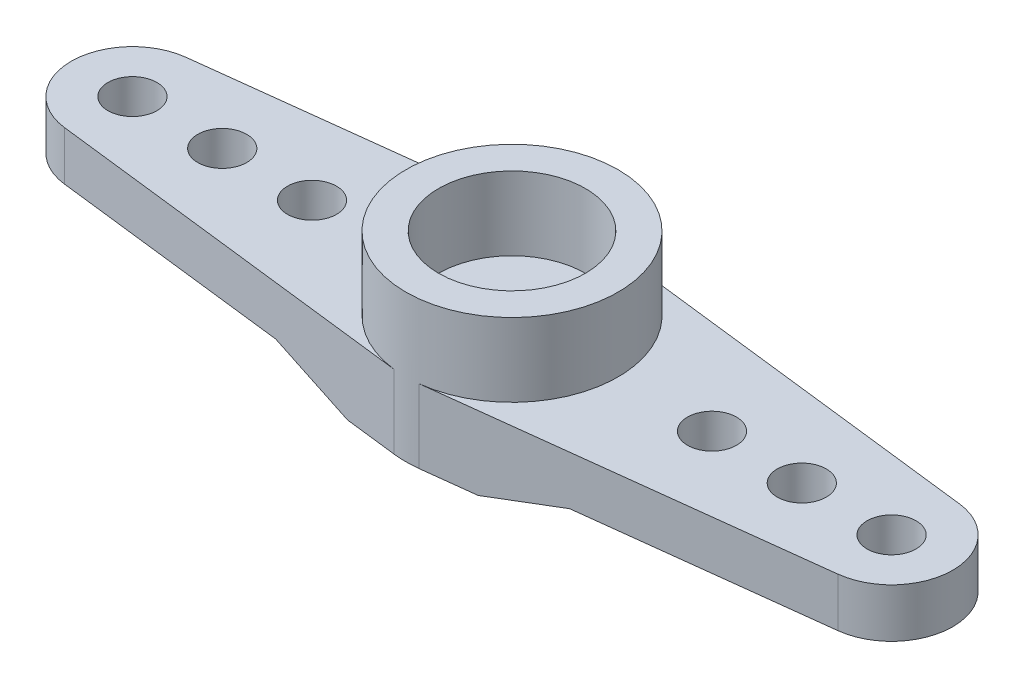
SolidWorks part; units mm, degrees
ref_plane "Alzado" through (0, 0, 0) normal (0, 0, 1) x (1, 0, 0)
ref_plane "Planta" through (0, 0, 0) normal (0, 1, 0) x (1, 0, 0)
ref_plane "Vista lateral" through (0, 0, 0) normal (1, 0, 0) x (0, 0, -1)
sketch "Croquis1" plane through (0, 0, 0) normal (0, 1, 0) x (1, 0, 0)
  line L0 (-30.9646, 0) -> (30.9646, 0) construction
  line L1 (0, -23.5018) -> (0, 23.5018) construction
  line L2 (0.7688, 6.4544) -> (23.6935, 3.7237)
  line L3 (0.7688, -6.4544) -> (23.6935, -3.7237)
  line L4 (-0.7688, -6.4544) -> (-23.6935, -3.7237)
  line L5 (-0.7688, 6.4544) -> (-23.6935, 3.7237)
  arc A0 (-0.7688, -6.4544) -> (0.7688, -6.4544) centre (0, 0) ccw
  arc A1 (23.6935, -3.7237) -> (23.6935, 3.7237) centre (23.25, 0) ccw
  arc A2 (0.7688, 6.4544) -> (-0.7688, 6.4544) centre (0, 0) ccw
  arc A3 (-23.6935, -3.7237) -> (-23.6935, 3.7237) centre (-23.25, 0) cw
  point P6 (0, 0)
  point P11 (27, 0)
  dimension "D1" = 13
  dimension "D3" = 27
  dimension "D2" = 23.25
extrude "Saliente-Extruir1" add sketch "Croquis1" along normal blind 3
sketch "Croquis2" plane through (0, 3, 0) normal (0, 1, 0) x (1, 0, 0)
  arc A0 (0.7688, 6.4544) -> (-0.7688, 6.4544) centre (0, 0) ccw construction
  arc A1 (0.7688, 6.4544) -> (-0.7688, 6.4544) centre (0, 0) ccw construction
  circle A2 centre (0, 0) radius 6.5
  circle A3 centre (0, 0) radius 4.5
  dimension "D1" = 9
extrude "Saliente-Extruir2" add sketch "Croquis2" along normal blind 4.5
sketch "Croquis3" plane through (0, 0, 0) normal (0, -1, 0) x (1, 0, 0)
  line L0 (23.6935, -3.7237) -> (0.7688, -6.4544) construction
  line L1 (-0.7688, -6.4544) -> (-23.6935, -3.7237) construction
  line L2 (0.7688, 6.4544) -> (23.6935, 3.7237) construction
  line L3 (-23.6935, 3.7237) -> (-0.7688, 6.4544) construction
  line L4 (4, -6.0695) -> (0.7688, -6.4544)
  line L5 (-0.7688, -6.4544) -> (-4, -6.0695)
  line L6 (0.7688, 6.4544) -> (4, 6.0695)
  line L7 (-4, 6.0695) -> (-0.7688, 6.4544)
  line L8 (0, 8.9582) -> (0, -10.3937) construction
  line L9 (-4, 6.0695) -> (-4, -6.0695)
  line L10 (4, 6.0695) -> (4, -6.0695)
  arc A0 (-0.7688, -6.4544) -> (0.7688, -6.4544) centre (0, 0) ccw construction
  arc A1 (0.7688, 6.4544) -> (-0.7688, 6.4544) centre (0, 0) ccw construction
  arc A2 (-0.7688, -6.4544) -> (0.7688, -6.4544) centre (0, 0) ccw
  arc A3 (0.7688, 6.4544) -> (-0.7688, 6.4544) centre (0, 0) ccw
  dimension "D1" = 4
extrude "Saliente-Extruir3" add sketch "Croquis3" along normal blind 1.5
sketch "Croquis4" plane through (0, 0, 0) normal (0, 0, 1) x (1, 0, 0)
  line L1 (4, -1.5) -> (4, 0) construction
  line L2 (-4, -1.5) -> (-4, 0) construction
  line L3 (-23.6935, 0) -> (-4, 0) construction
  line L6 (-4, -1.5) -> (-4, 0)
  line L7 (-9, 0) -> (-4, 0)
  line L8 (0, -4.7923) -> (0, 8.7073) construction
  line L9 (-4, -1.5) -> (-9, 0)
  dimension "D1" = 9
extrude "Saliente-Extruir4" add sketch "Croquis4" along normal up to surface and the other way up to surface up to face at (-9.4875, 0.5, 5.4158) other way up to face at (-9.4875, 0.5, -5.4158)
sketch "Croquis5" plane through (0, 0, 0) normal (0, 0, 1) x (1, 0, 0)
  line L0 (4, 0) -> (23.6935, 0) construction
  line L1 (4, -1.5) -> (4, 0) construction
  line L2 (4, 0) -> (9, 0)
  line L3 (4, -1.5) -> (4, 0)
  line L4 (4, -1.5) -> (9, 0)
  dimension "D1" = 9
extrude "Saliente-Extruir5" add sketch "Croquis5" along normal up to surface and the other way up to surface up to face at (9.4875, 0.5, 5.4158) other way up to face at (9.4875, 0.5, -5.4158)
sketch "Croquis7" plane through (0, -1.5, 0) normal (0, -1, 0) x (1, 0, 0)
  circle A0 centre (0, 0) radius 3.5
  dimension "D1" = 7
extrude "Cortar-Extruir1" cut sketch "Croquis7" against normal blind 2.5
sketch "Croquis8" plane through (0, 1, 0) normal (0, -1, 0) x (1, 0, 0)
  line L0 (-29.5937, 0) -> (29.5937, 0) construction
  line L1 (0, 7.9546) -> (0, -9.7642) construction
  circle A0 centre (0, 0) radius 1.5
  circle A1 centre (12.25, 0) radius 1.5
  circle A2 centre (17.75, 0) radius 1.5
  circle A3 centre (23.25, 0) radius 1.5
  circle A4 centre (-23.25, 0) radius 1.5
  circle A5 centre (-17.75, 0) radius 1.5
  circle A6 centre (-12.25, 0) radius 1.5
  dimension "D1" = 3
  dimension "D2" = 12.25
  dimension "D4" = 23.25
  dimension "D3" = 17.75
extrude "Cortar-Extruir2" cut sketch "Croquis8" against normal through all both and the other way through all
